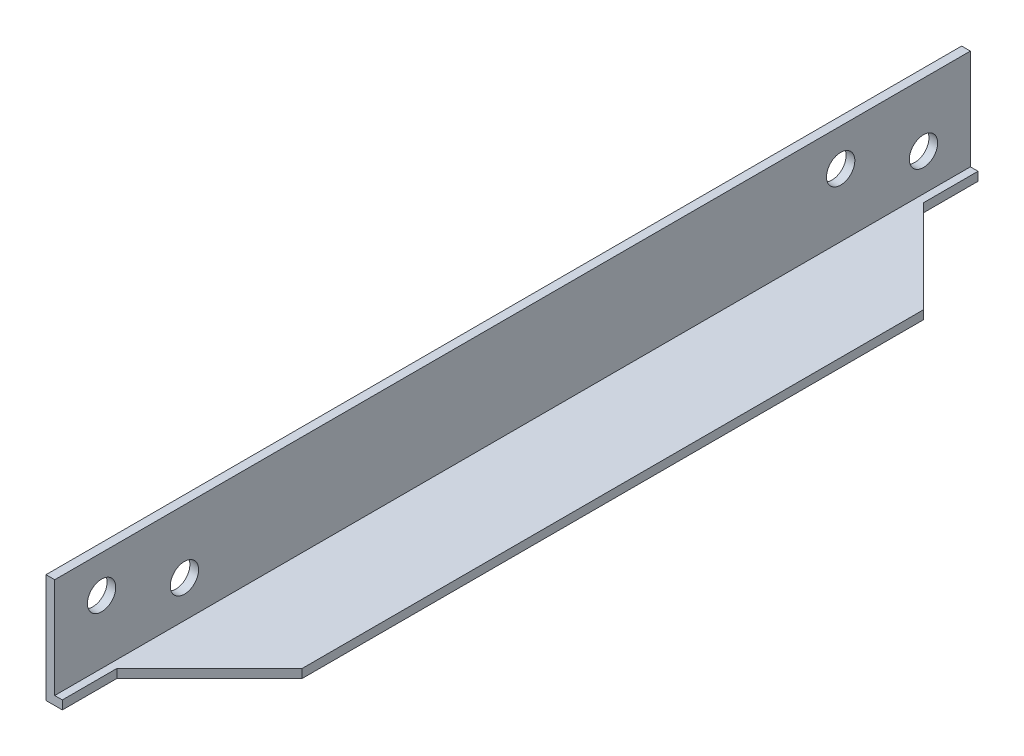
SolidWorks part; units mm, degrees
ref_plane "前视基准面" through (0, 0, 0) normal (0, 0, 1) x (1, 0, 0)
ref_plane "上视基准面" through (0, 0, 0) normal (0, 1, 0) x (1, 0, 0)
ref_plane "右视基准面" through (0, 0, 0) normal (1, 0, 0) x (0, 0, -1)
sketch "草图1" plane through (0, 0, 0) normal (0, 0, 1) x (1, 0, 0)
  line L1 (0, 0) -> (100, 0)
  line L2 (0, 0) -> (0, 100)
  line L3 (0, 100) -> (100, 100)
  line L4 (100, 0) -> (100, 100)
  dimension "D1" = 100
  dimension "D2" = 100
extrude "凸台-拉伸1" add sketch "草图1" along normal blind 840
sketch "草图2" plane through (0, 0, 840) normal (0, 0, 1) x (1, 0, 0)
  line L0 (0, 100) -> (0, 0) construction
  line L1 (100, 100) -> (8, 100)
  line L2 (100, 100) -> (100, 8)
  line L3 (100, 8) -> (8, 8)
  line L4 (8, 100) -> (8, 8)
  line L5 (0, 0) -> (100, 0) construction
  dimension "D1" = 8
  dimension "D2" = 8
extrude "切除-拉伸1" cut sketch "草图2" against normal through all
sketch "草图3" plane through (0, 0, 0) normal (-1, 0, 0) x (0, 0, 1)
  line L0 (0, 100) -> (0, 0) construction
  line L2 (840, 0) -> (0, 0) construction
  line L4 (840, 100) -> (840, 8) construction
  circle A0 centre (43, 42) radius 13
  circle A1 centre (119, 66) radius 13
  circle A2 centre (797, 66) radius 13
  circle A3 centre (721, 42) radius 13
  dimension "D1" = 26
  dimension "D2" = 43
  dimension "D3" = 76
  dimension "D4" = 42
  dimension "D5" = 24
  dimension "D6" = 43
  dimension "D7" = 76
extrude "切除-拉伸2" cut sketch "草图3" against normal through all
sketch "草图4" plane through (0, 8, 0) normal (0, 1, 0) x (1, 0, 0)
  line L0 (15, 0) -> (15, -50)
  line L1 (8, 0) -> (100, 0) construction
  line L2 (15, -50) -> (100, -135)
  line L3 (100, 0) -> (100, -840) construction
  line L4 (100, -135) -> (100, 0)
  line L5 (100, 0) -> (15, 0)
  line L6 (15, -840) -> (15, -790)
  line L7 (8, -840) -> (100, -840) construction
  line L8 (15, -790) -> (100, -705)
  line L9 (100, -705) -> (100, -840)
  line L10 (100, -840) -> (15, -840)
  line L11 (0, -840) -> (0, 0) construction
  dimension "D1" = 15
  dimension "D2" = 50
  dimension "D3" = 45
extrude "切除-拉伸3" cut sketch "草图4" against normal through all
